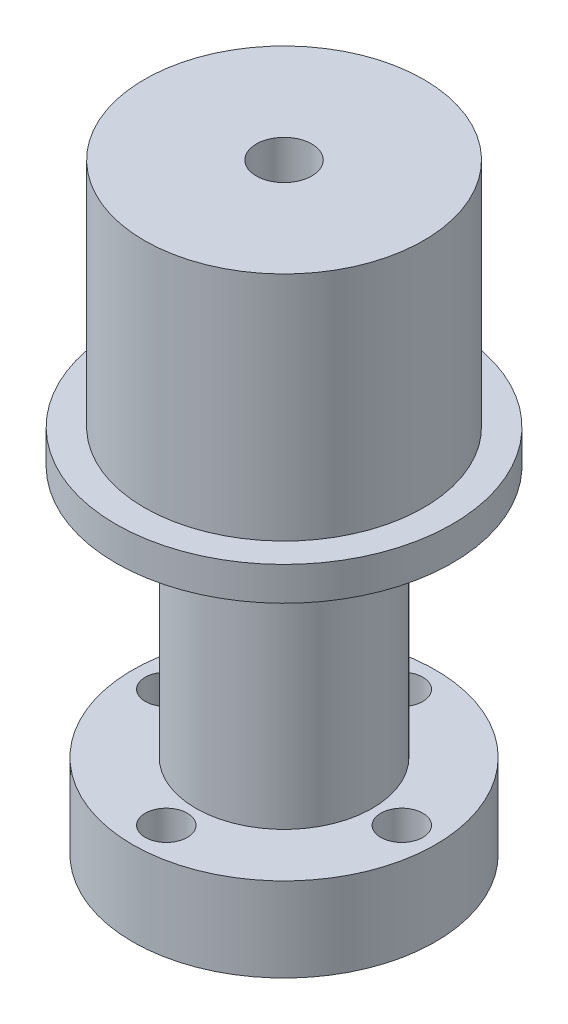
SolidWorks part; units mm, degrees
ref_plane "前视基准面" through (0, 0, 0) normal (0, 0, 1) x (1, 0, 0)
ref_plane "上视基准面" through (0, 0, 0) normal (0, 1, 0) x (1, 0, 0)
ref_plane "右视基准面" through (0, 0, 0) normal (1, 0, 0) x (0, 0, -1)
sketch "草图1" plane through (0, 0, 0) normal (0, 1, 0) x (1, 0, 0)
  circle A0 centre (0, 0) radius 9
  dimension "D1" = 18
extrude "凸台-拉伸1" add sketch "草图1" along normal blind 5
sketch "草图2" plane through (0, 0, 0) normal (0, -1, 0) x (1, 0, 0)
  line L0 (-9, 0) -> (9, 0) construction
  line L1 (0, 9) -> (0, -9) construction
  circle A0 centre (0, 0) radius 9 construction
  point P8 (0, 7)
  point P9 (-7, 0)
  point P10 (0, -7)
  point P11 (7, 0)
  dimension "D1" = 14
  dimension "D2" = 14
sketch "草图3" plane through (0, 5, 0) normal (0, 1, 0) x (1, 0, 0)
  circle A0 centre (0, 0) radius 5.25
  dimension "D1" = 10.5
extrude "凸台-拉伸2" add sketch "草图3" along normal blind 15
sketch "草图4" plane through (0, 20, 0) normal (0, 1, 0) x (1, 0, 0)
  circle A0 centre (0, 0) radius 10
  dimension "D1" = 20
extrude "凸台-拉伸4" add sketch "草图4" along normal blind 2
sketch "草图5" plane through (0, 22, 0) normal (0, 1, 0) x (1, 0, 0)
  circle A0 centre (0, 0) radius 8.3
  dimension "D1" = 16.6
extrude "凸台-拉伸5" add sketch "草图5" along normal blind 13.75
hole_wizard "M3 螺纹孔1" positions "草图6" profile "草图7" tap size "M3" standard "GB"
sketch "草图6" plane through (0, 0, 0) normal (0, -1, 0) x (-1, 0, 0)
  point P0 (0, 7)
  point P3 (-7, 0)
  point P6 (7, 0)
  point P9 (0, -7)
sketch "草图7" plane through (0, 0, -7) normal (1, 0, 0) x (0, 0, -1)
  line L0 (0, 0) -> (0, 5)
  line L1 (0, 5) -> (1.25, 5)
  line L2 (1.25, 5) -> (1.25, 0)
  line L5 (1.25, 0) -> (0, 0)
  line L11 (0, -6.35) -> (0, 107.95) construction
  dimension "通孔螺纹孔钻头直径" = 2.5
  dimension "通孔螺纹孔钻头深度" = 5
cosmetic thread "孔螺蚊线1" parameters "D2"=3
cosmetic thread "孔螺蚊线2" parameters "D2"=3
cosmetic thread "孔螺蚊线3" parameters "D2"=3
cosmetic thread "孔螺蚊线4" parameters "D2"=3
sketch "草图8" plane through (0, 0, 0) normal (0, -1, 0) x (1, 0, 0)
  circle A0 centre (0, 0) radius 5
  dimension "D1" = 10
extrude "凸台-拉伸6" add sketch "草图8" along normal blind 2
hole_wizard "M4 螺纹孔3" positions "草图14" profile "草图15" tap size "M4" standard "GB"
sketch "草图14" plane through (0, 35.75, 0) normal (0, 1, 0) x (1, 0, 0)
  point P0 (0, 0)
sketch "草图15" plane through (0, 35.75, 0) normal (1, 0, 0) x (0, 0, 1)
  line L0 (0, 0) -> (0, 11.0914)
  line L1 (0, 11.0914) -> (1.65, 10.1)
  line L2 (1.65, 10.1) -> (1.65, 0)
  line L5 (1.65, 0) -> (0, 0)
  line L10 (0, 11.0914) -> (-1.65, 10.1) construction
  line L11 (0, -6.35) -> (0, 107.95) construction
  dimension "螺纹孔钻头直径" = 3.3
  dimension "螺纹孔钻头深度" = 10.1
  dimension "导头角度" = 118
cosmetic thread "孔螺蚊线7" parameters "D1"=8, "D2"=4
